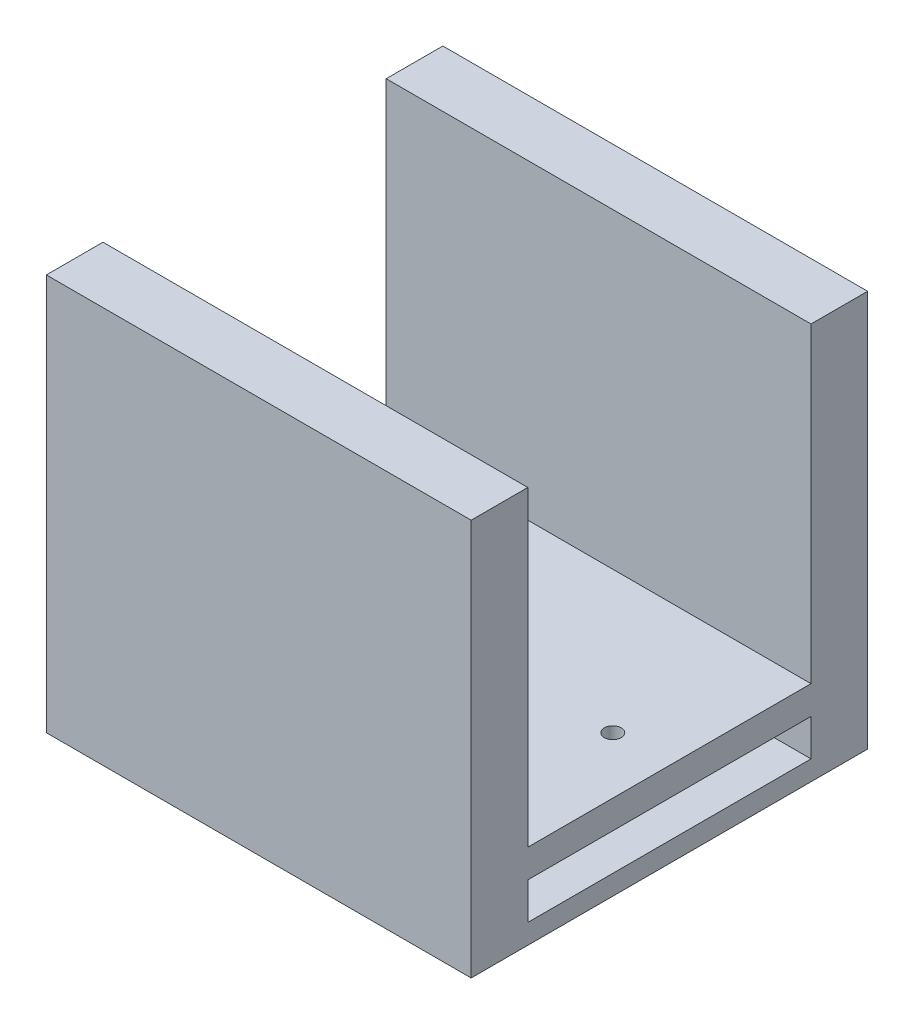
SolidWorks part; units mm, degrees
ref_plane "前基準面" through (0, 0, 0) normal (0, 0, 1) x (1, 0, 0)
ref_plane "上基準面" through (0, 0, 0) normal (0, 1, 0) x (1, 0, 0)
ref_plane "右基準面" through (0, 0, 0) normal (1, 0, 0) x (0, 0, -1)
sketch "草圖2" plane through (0, 0, 0) normal (0, 1, 0) x (1, 0, 0)
  line L1 (-59.1429, 35.7857) -> (90.8571, 35.7857)
  line L2 (-59.1429, 35.7857) -> (-59.1429, -104.2143)
  line L3 (-59.1429, -104.2143) -> (90.8571, -104.2143)
  line L4 (90.8571, 35.7857) -> (90.8571, -104.2143)
  dimension "D1" = 150
  dimension "D2" = 140
extrude "填料-伸長1" add sketch "草圖2" along normal blind 140
sketch "草圖3" plane through (0, 140, 0) normal (0, 1, 0) x (1, 0, 0)
  line L0 (90.8571, 35.7857) -> (-59.1429, 35.7857) construction
  line L1 (-59.1429, 15.7857) -> (90.8571, 15.7857)
  line L2 (-59.1429, 15.7857) -> (-59.1429, -84.2143)
  line L3 (-59.1429, -84.2143) -> (90.8571, -84.2143)
  line L4 (90.8571, 15.7857) -> (90.8571, -84.2143)
  line L5 (-59.1429, -104.2143) -> (90.8571, -104.2143) construction
  line L6 (-59.1429, 35.7857) -> (-59.1429, -104.2143) construction
  line L7 (90.8571, -104.2143) -> (90.8571, 35.7857) construction
  dimension "D1" = 20
  dimension "D2" = 20
  dimension "D3" = 0
  dimension "D4" = 0
extrude "除料-伸長1" cut sketch "草圖3" against normal blind 110
sketch "草圖4" plane through (90.8571, 0, 0) normal (1, 0, 0) x (0, 0, -1)
  line L0 (-104.2143, 140) -> (-104.2143, 0) construction
  line L1 (-84.2143, 20) -> (15.7857, 20)
  line L2 (-84.2143, 20) -> (-84.2143, 7)
  line L3 (-84.2143, 7) -> (15.7857, 7)
  line L4 (15.7857, 20) -> (15.7857, 7)
  line L5 (-84.2143, 30) -> (15.7857, 30) construction
  line L6 (-104.2143, 0) -> (35.7857, 0) construction
  dimension "D1" = 100
  dimension "D2" = 20
  dimension "D3" = 10
  dimension "D4" = 7
extrude "除料-伸長2" cut sketch "草圖4" against normal through all
sketch "草圖5" plane through (0, 30, 0) normal (0, 1, 0) x (1, 0, 0)
  line L0 (90.8571, -34.2143) -> (70.8571, -34.2143) construction
  line L1 (90.8571, -84.2143) -> (90.8571, 15.7857) construction
  circle A0 centre (70.8571, -34.2143) radius 3
  dimension "D2" = 6
  dimension "D1" = 20
extrude "除料-伸長3" cut sketch "草圖5" against normal blind 50
sketch "草圖6" plane through (0, 30, 0) normal (0, 1, 0) x (1, 0, 0)
  line L0 (-59.1429, -34.2143) -> (-29.1429, -34.2143) construction
  line L1 (-59.1429, 15.7857) -> (-59.1429, -84.2143) construction
  circle A0 centre (-29.1429, -34.2143) radius 3
  dimension "D1" = 6
extrude "除料-伸長4" cut sketch "草圖6" against normal through all
